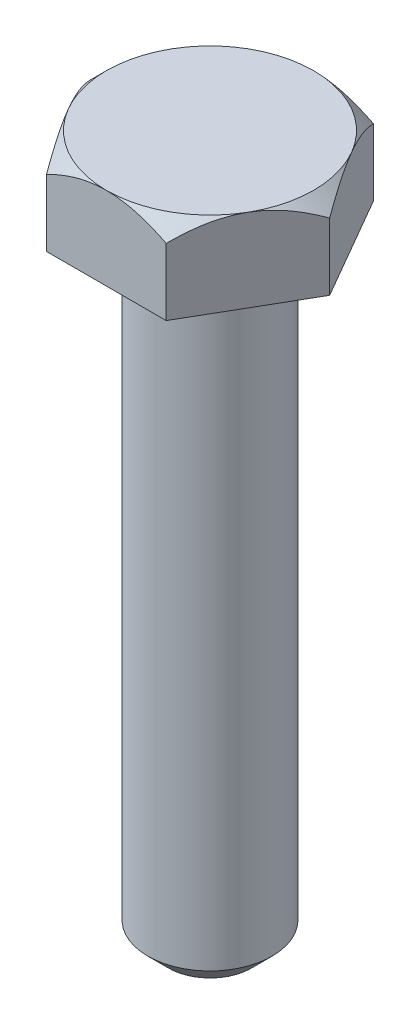
SolidWorks part; units mm, degrees
material "1.0715 (11SMn30)"
ref_plane "Płaszczyzna przednia" through (0, 0, 0) normal (0, 0, 1) x (1, 0, 0)
ref_plane "Płaszczyzna górna" through (0, 0, 0) normal (0, 1, 0) x (1, 0, 0)
ref_plane "Płaszczyzna prawa" through (0, 0, 0) normal (1, 0, 0) x (0, 0, -1)
sketch "Szkic1" plane through (0, 0, 0) normal (0, 1, 0) x (1, 0, 0)
  circle A0 centre (0, 0) radius 3
  dimension "D1" = 6
extrude "Dodanie-wyciągnięcie1" add sketch "Szkic1" against normal blind 30
sketch "Szkic2" plane through (0, 0, 0) normal (0, 1, 0) x (1, 0, 0)
  line L1 (5.7735, 0) -> (2.8868, 5)
  line L2 (2.8868, 5) -> (-2.8868, 5)
  line L3 (-2.8868, 5) -> (-5.7735, 0)
  line L4 (-5.7735, 0) -> (-2.8868, -5)
  line L5 (-2.8868, -5) -> (2.8868, -5)
  line L6 (2.8868, -5) -> (5.7735, 0)
  circle A0 centre (0, 0) radius 5 construction
  dimension "D1" = 10
extrude "Dodanie-wyciągnięcie2" add sketch "Szkic2" along normal blind 4
sketch "Szkic3" plane through (0, 4, 0) normal (0, 1, 0) x (1, 0, 0)
  line L0 (-2.8868, 5) -> (-5.7735, 0) construction
  circle A0 centre (0, 0) radius 5
sketch "Szkic4" plane through (0, 0, 0) normal (0, 0, 1) x (1, 0, 0)
  line L0 (5.7735, 3.2265) -> (5, 4)
  line L2 (5, 4) -> (-5, 4) construction
  line L3 (5, 4) -> (5.7735, 4)
  line L4 (5.7735, 4) -> (5.7735, 3.2265)
sketch "Szkic5" plane through (0, 0, 0) normal (0, 0, 1) x (1, 0, 0)
  line L0 (0, 4) -> (0, -30) construction
  line L1 (5, 4) -> (-5, 4) construction
  line L2 (-3, -30) -> (3, -30) construction
revolve "Wycięcie-obrót1" cut sketch "Szkic4" angle 360 about L0
chamfer "Sfazowanie1" distance 1 angle 45 1 edges at (0, -30, 3)
